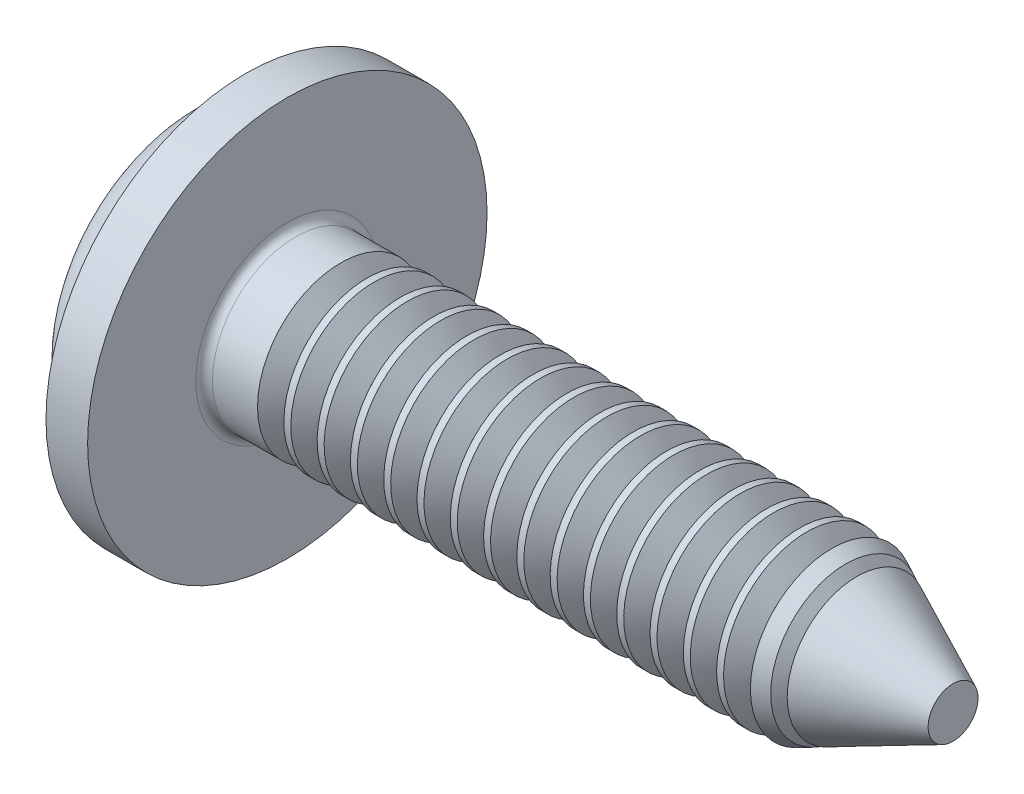
SolidWorks part; units mm, degrees
material "Aço NB 1045"
ref_plane "Plane1" through (0, 0, 0) normal (0, 0, 1) x (1, 0, 0)
ref_plane "Plane2" through (0, 0, 0) normal (0, 1, 0) x (1, 0, 0)
ref_plane "Plane3" through (0, 0, 0) normal (1, 0, 0) x (0, 0, -1)
sketch "BodySke" plane through (0, 0, 0) normal (0, 0, 1) x (1, 0, 0)
  line L0 (1.6, 1) -> (1.6, 2)
  line L1 (1.8, 6.35) -> (1.8, -3.175) construction
  line L2 (-25.4, 0) -> (127, 0) construction
  line L3 (9.6, 0) -> (0, 0)
  line L4 (1.6, 1) -> (9.6, 1)
  line L5 (9.6, 1) -> (9.6, 0)
  line L6 (1.1, 2) -> (1.6, 2)
  line L8 (1.6, 6.35) -> (1.6, -3.175) construction
  arc A0 (0.3941, 1.5765) -> (0, 0) centre (3.35, 0) ccw
  arc A2 (0.3941, 1.5765) -> (1.1, 2) centre (1.1, 1.2) cw
  dimension "D2" = 0.8
  dimension "Length" = 8
  dimension "Head_ht" = 1.6
  dimension "Head_dia" = 4
  dimension "Advance" = 0.4
  dimension "Thread_nom" = 8
  dimension "Diameter" = 2
  dimension "D1" = 0.5
revolve "Base-Revolve" add sketch "BodySke"
cosmetic thread "ThreadCosmetic" [suppressed]
fillet "Fillet1" radius 0.1 1 edges at (1.6, 0, 1)
sketch "Sketch3" plane through (0, 0, 0) normal (1, 0, 0) x (0, 0, -1)
  line L0 (0.24, -1.05) -> (-0.24, -1.05)
  line L1 (0.24, -1.05) -> (0.24, 1.05)
  line L2 (-0.24, 1.05) -> (0.24, 1.05)
  line L3 (-0.24, 1.05) -> (-0.24, -1.05)
  dimension "Cross_dia" = 2.1
  dimension "D1" = 1.05
  dimension "Cross_width" = 0.48
  dimension "D2" = 0.24
ref_plane "Plane4" through (1.42, 0, 0) normal (1, 0, 0) x (0, 0, -1)
sketch "Sketch4" plane through (1.42, 0, 0) normal (1, 0, 0) x (0, 0, -1)
  line L0 (0.24, -0.342) -> (-0.24, -0.342)
  line L1 (0.24, -0.342) -> (0.24, 0.342)
  line L2 (-0.24, 0.342) -> (0.24, 0.342)
  line L3 (-0.24, 0.342) -> (-0.24, -0.342)
  dimension "D1" = 0.48
  dimension "D2" = 0.684
  dimension "D3" = 0.24
  dimension "D4" = 0.342
loft "Recess" cut profiles "Sketch3", "Sketch4"
pattern_circular "RecPat" count 2 every 90 about axis through (0, 0, 0) along (1, 0, 0) of "Recess"
sketch "RecCorSke" plane through (0, 0, 0) normal (0, 0, 1) x (1, 0, 0)
  line L0 (-3.175, 0) -> (15.875, 0) construction
  line L1 (-25.4, 0) -> (127, 0) construction
  line L2 (0, 0) -> (0, 0.4548)
  line L3 (0, 0.4548) -> (1.42, 0.3555)
  line L4 (1.42, 0.3555) -> (1.5355, 0)
  line L5 (1.5355, 0) -> (0, 0)
  dimension "Diameter" = 0.711
  dimension "Depth" = 1.42
  dimension "Draft_angle" = 4
  dimension "Bottom_angle" = 18
revolve "RecessCore" cut sketch "RecCorSke" angle 360 about L0
sketch "ThdSchSke" plane through (0, 0, 0) normal (0, 0, 1) x (1, 0, 0)
  line L0 (2.4, -0.774) -> (2.2418, -1)
  line L1 (2.4, -0.774) -> (2.5582, -1)
  line L2 (2.5582, -1) -> (2.5582, -1.25)
  line L3 (-3.175, 0) -> (5.1513, 0) construction
  line L5 (2.5582, -1.25) -> (2.2418, -1.25)
  line L6 (2.2418, -1.25) -> (2.2418, -1)
  dimension "Diameter" = 2
  dimension "SideAngle" = 55
  dimension "VeeAngle" = 70
  dimension "Thread_minor" = 1.548
  dimension "Overcut" = 2.5
  dimension "Start" = 2.4
revolve "ThreadSchematic" cut sketch "ThdSchSke" angle 360 about L3
pattern_linear "ThdSchPat" count 19 spacing 0.4 along (1, 0, 0) of "ThreadSchematic"
sketch "Esboço1" plane through (1.6, 0, 0) normal (1, 0, 0) x (0, 0, -1)
  circle A0 centre (0, 0) radius 2.4
  dimension "D1" = 4.8
extrude "Ressalto-extrusão1" add sketch "Esboço1" against normal blind 0.5
sketch "Esboço2" plane through (0, 0, 0) normal (0, 1, 0) x (1, 0, 0)
  line L0 (0, 0) -> (9.6, 0) construction
  line L1 (9.6, -0.774) -> (9.6, 0.774) construction
  line L2 (9.6, 0.3) -> (8.1, 1)
  line L4 (8.1, 1) -> (9.6, 1)
  line L5 (9.6, 1) -> (9.6, 0.3)
  line L6 (7.4418, 1) -> (7.3582, 1) construction
  dimension "D1" = 1.5
  dimension "D2" = 0.6
revolve "Corte-Revolução1" cut sketch "Esboço2" angle 360 about L0
scale "Echelle1" bodies to scale 106 scale about centroid uniform scaling yes scale factor 1
scale "Echelle2" bodies to scale 107 scale about origin uniform scaling yes scale factor 2
scale "Echelle3" bodies to scale 108 scale about origin uniform scaling yes scale factor 0.5
scale "Echelle4" bodies to scale 109 scale about origin uniform scaling yes scale factor 0.5
equation "\"D1@Sketch3\" = \"Cross_dia@Sketch3\" / 2"
equation "\"D2@Sketch3\" = \"Cross_width@Sketch3\" / 2"
equation "\"Depth@RecCorSke\" = \"Cross_depth@Plane4\""
equation "\"D1@Sketch4\" = \"Cross_width@Sketch3\""
equation "\"D2@Sketch4\" = \"Cross_dia@Sketch3\" - 2.0 * \"Cross_depth@Plane4\" * tan(26.5  * 0.017453292)"
equation "\"D3@Sketch4\" = \"D1@Sketch4\" / 2"
equation "\"D4@Sketch4\" = \"D2@Sketch4\" / 2"
equation "\"Thread_length@ThreadCosmetic\" = ((sgn( (\"Length@BodySke\" - \"Advance@BodySke\" * 2.0 ) - \"Thread_nom@BodySke\" )-1)*( (\"Length@BodySke\" - \"Advance@BodySke\" * 2.0 ) - \"Thread_nom@BodySke\" ))/-2+ \"Thread_nom@BodySke\""
equation "\"Thread_minor@ThdSchSke\" = \"Thread_minor@ThreadCosmetic\""
equation "\"Diameter@ThdSchSke\" = \"Diameter@BodySke\""
equation "\"Overcut@ThdSchSke\" = \"Diameter@BodySke\" * 1.25"
equation "\"Start@ThdSchSke\" = \"Head_ht@BodySke\" + \"Length@BodySke\" - \"Thread_length@ThreadCosmetic\"  '---Non-countersunk---"
equation "\"Num_threads@ThdSchPat\" = int( \"Thread_length@ThreadCosmetic\" / \"Advance@BodySke\" + 0.999 )  + 1"
equation "\"Advance@ThdSchPat\" = \"Thread_length@ThreadCosmetic\" /  (\"Num_threads@ThdSchPat\" - 1) 'relax it"
